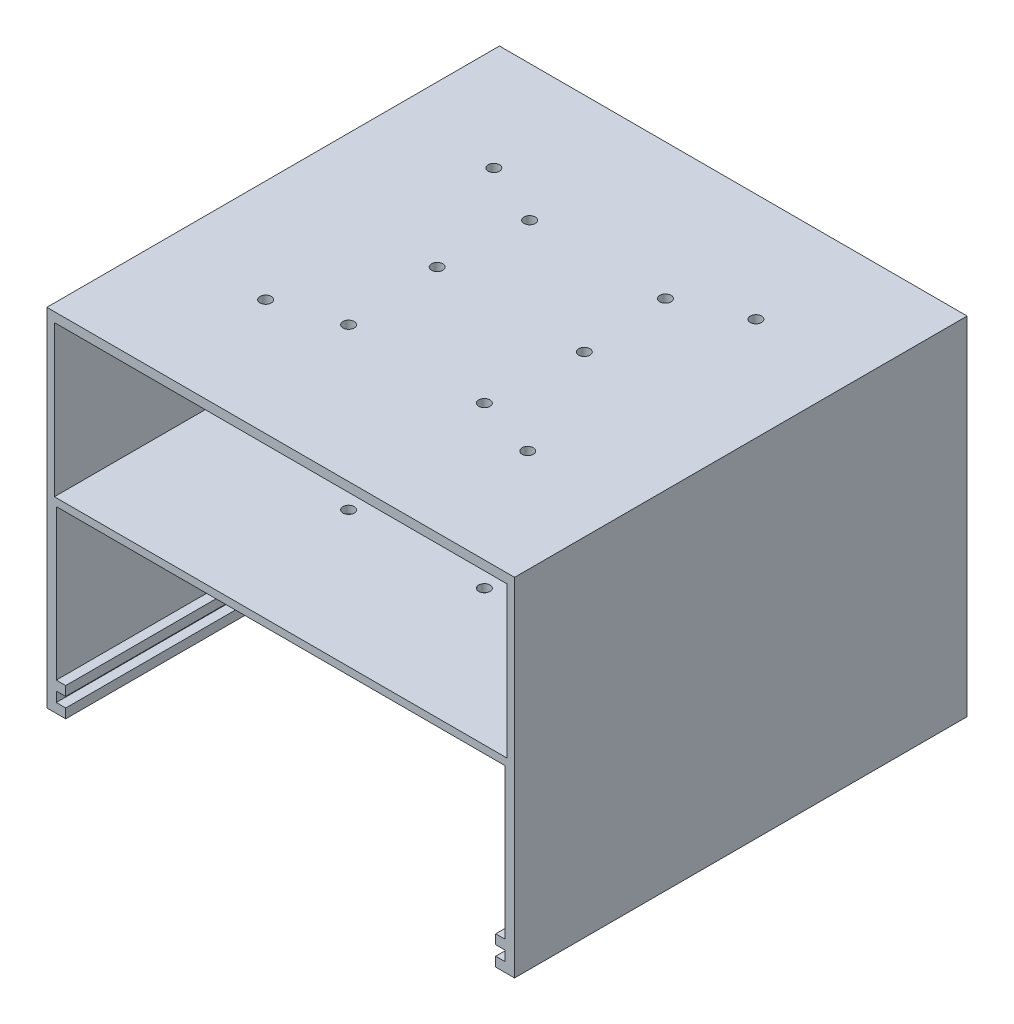
SolidWorks part; units mm, degrees
ref_plane "前视基准面" through (0, 0, 0) normal (0, 0, 1) x (1, 0, 0)
ref_plane "上视基准面" through (0, 0, 0) normal (0, 1, 0) x (1, 0, 0)
ref_plane "右视基准面" through (0, 0, 0) normal (1, 0, 0) x (0, 0, -1)
sketch "草图2" plane through (0, 0, 0) normal (0, 1, 0) x (1, 0, 0)
  line L1 (-62, 60) -> (62, 60)
  line L2 (-62, 60) -> (-62, -60)
  line L3 (-62, -60) -> (62, -60)
  line L4 (62, 60) -> (62, -60)
  line L5 (-62, 60) -> (62, -60) construction
  line L6 (-62, -60) -> (62, 60) construction
  point P0 (0, 0)
  dimension "D1" = 124
  dimension "D2" = 120
extrude "凸台-拉伸1" add sketch "草图2" along normal blind 2
sketch "草图3" plane through (0, 2, 0) normal (0, 1, 0) x (1, 0, 0)
  line L0 (-62, -60) -> (62, -60) construction
  line L1 (-62, 60) -> (-60, 60)
  line L2 (-62, 60) -> (-62, -60)
  line L3 (-62, -60) -> (-60, -60)
  line L4 (-60, 60) -> (-60, -60)
  line L6 (62, 60) -> (60, 60)
  line L7 (62, 60) -> (62, -60)
  line L8 (62, -60) -> (60, -60)
  line L9 (60, 60) -> (60, -60)
  dimension "D1" = 2
  dimension "D2" = 2
extrude "凸台-拉伸2" add sketch "草图3" along normal blind 40
sketch "草图4" plane through (0, 2, 0) normal (0, 1, 0) x (1, 0, 0)
  line L0 (60, 60) -> (60, -60) construction
  line L1 (-60, 60) -> (60, 60)
  line L2 (-60, 60) -> (-60, 58)
  line L3 (-60, 58) -> (60, 58)
  line L4 (60, 60) -> (60, 58)
  dimension "D1" = 2
extrude "凸台-拉伸3" add sketch "草图4" along normal blind 5
sketch "草图6" plane through (0, 42, 0) normal (0, 1, 0) x (1, 0, 0)
  line L1 (-62, 60) -> (62, 60)
  line L2 (-62, 60) -> (-62, -60)
  line L3 (-62, -60) -> (62, -60)
  line L4 (62, 60) -> (62, -60)
extrude "凸台-拉伸4" add sketch "草图6" along normal blind 2.5
sketch "草图9" plane through (0, 44.5, 0) normal (0, 1, 0) x (1, 0, 0)
  line L1 (-62, 60) -> (-62, -60) construction
  line L2 (-62, 35) -> (62, 35)
  line L3 (-62, 35) -> (-62, 33.5)
  line L4 (-62, 33.5) -> (62, 33.5)
  line L5 (62, 35) -> (62, 33.5)
  line L6 (62, -60) -> (62, 60) construction
  line L7 (62, 60) -> (-62, 60) construction
  dimension "D1" = 1.5
  dimension "D2" = 25
extrude "凸台-拉伸5" add sketch "草图9" along normal blind 25
sketch "草图10" plane through (0, 0, -35) normal (0, 0, -1) x (-1, 0, 0)
  line L0 (-37.3016, 58) -> (-44.8167, 58) construction
  line L4 (-62, 69.5) -> (62, 69.5) construction
  line L5 (0, 70.5) -> (0, 58) construction
  circle A0 centre (-22.5, 58) radius 1.5
  circle A1 centre (22.5, 58) radius 1.5
  point P6 (0, 69.5)
  dimension "D1" = 45
  dimension "D2" = 22.5
extrude "切除-拉伸2" cut sketch "草图10" against normal blind 1.5
sketch "草图11" plane through (0, 44.5, 0) normal (0, 1, 0) x (1, 0, 0)
  line L0 (0, 33.5) -> (0, 8.5131) construction
  line L2 (-62, 33.5) -> (62, 33.5) construction
  line L3 (-62, 33.5) -> (62, 33.5) construction
  circle A0 centre (-19.5, 1) radius 1.5
  circle A2 centre (-18, 24) radius 1.5
  circle A3 centre (-18, -24) radius 1.5
  circle A4 centre (18, -24) radius 1.5
  circle A5 centre (19.5, 1) radius 1.5
  circle A6 centre (18, 24) radius 1.5
  dimension "D1" = 19.5
  dimension "D3" = 9.5
  dimension "D2" = 32.5
  dimension "D4" = 48
  dimension "D5" = 18
  dimension "D6" = 18
extrude "切除-拉伸3" cut sketch "草图11" against normal blind 51
sketch "草图12" plane through (0, 0, 0) normal (0, -1, 0) x (1, 0, 0)
  line L0 (62, -60) -> (-62, -60) construction
  line L1 (-62, 60) -> (-59.5, 60)
  line L2 (-62, 60) -> (-62, -60)
  line L3 (-62, -60) -> (-59.5, -60)
  line L4 (-59.5, 60) -> (-59.5, -60)
  line L5 (-62, 60) -> (62, 60) construction
  line L6 (62, -60) -> (59.5, -60)
  line L7 (62, -60) -> (62, 60)
  line L8 (62, 60) -> (59.5, 60)
  line L9 (59.5, -60) -> (59.5, 60)
  dimension "D1" = 2.5
  dimension "D2" = 2.5
extrude "凸台-拉伸6" add sketch "草图12" along normal blind 47.5
sketch "草图14" plane through (0, 0, -60) normal (0, 0, -1) x (-1, 0, 0)
  line L1 (-59.5, -47.5) -> (-57, -47.5)
  line L2 (-59.5, -47.5) -> (-59.5, -45)
  line L3 (-59.5, -45) -> (-57, -45)
  line L4 (-57, -47.5) -> (-57, -45)
  line L5 (59.5, -47.5) -> (57, -47.5)
  line L6 (59.5, -47.5) -> (59.5, -45)
  line L7 (59.5, -45) -> (57, -45)
  line L8 (57, -47.5) -> (57, -45)
  dimension "D1" = 2.5
  dimension "D2" = 2.5
  dimension "D3" = 2.5
  dimension "D4" = 2.5
extrude "凸台-拉伸8" add sketch "草图14" against normal blind 120
sketch "草图15" plane through (0, 0, 0) normal (0, -1, 0) x (1, 0, 0)
  line L0 (59.5, 60) -> (59.5, -60) construction
  line L1 (-59.5, -60) -> (59.5, -60)
  line L2 (-59.5, -60) -> (-59.5, -57)
  line L3 (-59.5, -57) -> (59.5, -57)
  line L4 (59.5, -60) -> (59.5, -57)
  dimension "D1" = 3
extrude "凸台-拉伸9" add sketch "草图15" along normal blind 47.5
sketch "草图16" plane through (-62, 0, 0) normal (-1, 0, 0) x (0, 0, 1)
  line L5 (39.7788, -10.5) -> (13.9482, -10.5) construction
  circle A2 centre (2.7788, 31.3663) radius 2.5
  circle A3 centre (2.7788, -33.6337) radius 2.5
  dimension "D3" = 65
extrude "切除-拉伸4" cut sketch "草图16" against normal blind 10
sketch "草图18" plane through (0, 0, 60) normal (0, 0, 1) x (1, 0, 0)
  line L0 (-59.5, -45) -> (-59.5, 0) construction
  line L1 (-59.5, -45) -> (-57, -45) construction
  line L2 (-59.5, -42.35) -> (-57, -42.35)
  line L3 (-59.5, -42.35) -> (-59.5, -39.85)
  line L4 (-59.5, -39.85) -> (-57, -39.85)
  line L5 (-57, -42.35) -> (-57, -39.85)
  line L6 (59.5, -45) -> (59.5, 0) construction
  line L7 (59.5, -42.35) -> (57, -42.35)
  line L8 (59.5, -42.35) -> (59.5, -39.85)
  line L9 (59.5, -39.85) -> (57, -39.85)
  line L10 (57, -42.35) -> (57, -39.85)
  line L11 (59.5, -45) -> (57, -45) construction
  dimension "D1" = 2.5
  dimension "D2" = 2.5
  dimension "D3" = 2.65
  dimension "D4" = 2.5
  dimension "D5" = 2.5
  dimension "D6" = 2.65
extrude "凸台-拉伸10" add sketch "草图18" against normal blind 120
sketch "草图19" plane through (0, 44.5, 0) normal (0, 1, 0) x (1, 0, 0)
  line L0 (0, 0) -> (64.5502, 0) construction
  line L1 (0, 0) -> (0, 19.3136) construction
  line L2 (0, 33.6355) -> (-32.5, 33.5)
  line L3 (-62, 33.5) -> (62, 33.5) construction
  line L4 (-32.5, 33.5) -> (-32.5, -31.5)
  line L5 (-32.5, -31.5) -> (32.5, -31.5)
  line L6 (32.5, -31.5) -> (32.5, 33.5)
  line L7 (32.5, 33.5) -> (0, 33.6355)
  line L8 (-37, 31.25) -> (-34.7402, 31.25) construction
  line L9 (-32.5, 33.5) -> (-37, 33.5)
  line L10 (-32.5, 33.5) -> (-32.5, 29)
  line L11 (-32.5, 29) -> (-37, 29)
  line L12 (-37, 33.5) -> (-37, 29)
  line L13 (-34.7402, 31.25) -> (-34.7402, 28.5803) construction
  line L15 (-32.5, -31.5) -> (-37, -31.5)
  line L16 (-32.5, -31.5) -> (-32.5, -27)
  line L17 (-32.5, -27) -> (-37, -27)
  line L18 (-37, -31.5) -> (-37, -27)
  line L19 (32.5, 33.5) -> (37, 33.5)
  line L20 (32.5, 33.5) -> (32.5, 29)
  line L21 (32.5, 29) -> (37, 29)
  line L22 (37, 33.5) -> (37, 29)
  line L23 (32.5, -31.5) -> (37, -31.5)
  line L24 (32.5, -31.5) -> (32.5, -27)
  line L25 (32.5, -27) -> (37, -27)
  line L26 (37, -31.5) -> (37, -27)
  circle A0 centre (-34.7402, 31.25) radius 1.5
  circle A1 centre (-34.75, -29.25) radius 1.5
  circle A2 centre (34.75, -29.25) radius 1.5
  circle A3 centre (34.75, 31.25) radius 1.5
  point P33 (0, 0)
  point P36 (34.4956, -31.5)
  point P37 (35.3316, 30.0036)
  point P38 (35.5702, 33.5)
  dimension "D6" = 4.5
  dimension "D8" = 2.25
  dimension "D13" = 2.25
  dimension "D1" = 65
  dimension "D2" = 32.5
  dimension "D3" = 65
  dimension "D4" = 4.5
  dimension "D5" = 4.5
  dimension "D7" = 4.5
  dimension "D9" = 4.5
  dimension "D10" = 4.5
  dimension "D11" = 4.5
  dimension "D12" = 4.5
  dimension "D14" = 2.25
  dimension "D15" = 2.25
  dimension "D16" = 2.25
  dimension "D17" = 69.5
sketch "草图20" plane through (0, 0, -35) normal (0, 0, -1) x (-1, 0, 0)
  line L1 (-62, 69.5) -> (62, 69.5)
  line L2 (-62, 69.5) -> (-62, 44.5)
  line L3 (-62, 44.5) -> (62, 44.5)
  line L4 (62, 69.5) -> (62, 44.5)
extrude "切除-拉伸5" cut sketch "草图20" against normal blind 10
extrude "切除-拉伸6" cut sketch "草图19" against normal blind 2.5 contours A1 | A0 | A3 | A2
